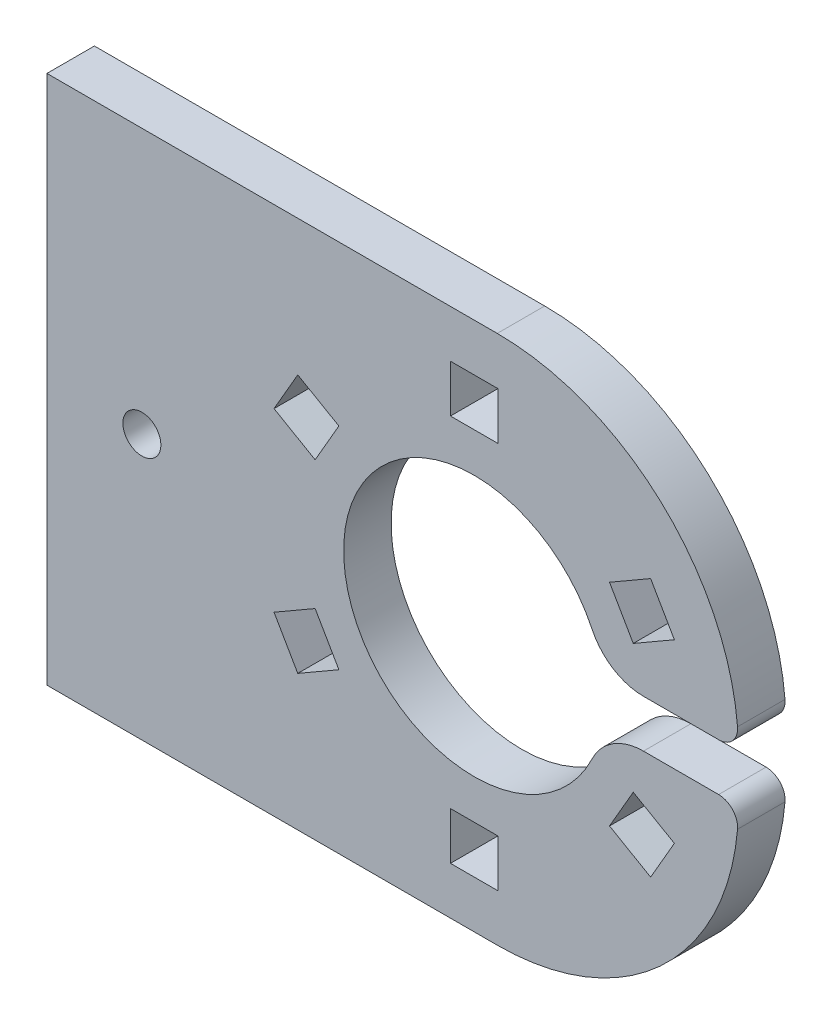
SolidWorks part; units mm, degrees
ref_plane "Plan de face" through (0, 0, 0) normal (0, 0, 1) x (1, 0, 0)
ref_plane "Plan de dessus" through (0, 0, 0) normal (0, 1, 0) x (1, 0, 0)
ref_plane "Plan de droite" through (0, 0, 0) normal (1, 0, 0) x (0, 0, -1)
sketch "Esquisse1" plane through (0, 0, 0) normal (0, 0, 1) x (1, 0, 0)
  line L0 (-62.8273, 27.9) -> (-62.8273, -27.9) construction
  line L1 (-72.8273, -27.9) -> (-72.8273, 27.9)
  line L2 (-52.8273, 27.9) -> (-52.8273, -27.9) construction
  line L4 (0, 2.5) -> (0, -2.5) construction
  line L5 (-72.8273, 27.9) -> (-25.4, 27.9)
  line L7 (-25.4, -27.9) -> (-72.8273, -27.9)
  line L17 (-60, 0) -> (0, 0) construction
  line L44 (-27.8273, 17.9) -> (-27.8273, 0) construction
  line L45 (-30.3273, 22.9) -> (-25.3273, 22.9)
  line L46 (-30.3273, 22.9) -> (-30.3273, 17.9)
  line L47 (-30.3273, 17.9) -> (-25.3273, 17.9)
  line L48 (-25.3273, 22.9) -> (-25.3273, 17.9)
  line L49 (-9.2453, 13.6151) -> (-6.7453, 9.2849)
  line L50 (-9.2453, 13.6151) -> (-13.5754, 11.1151)
  line L51 (-13.5754, 11.1151) -> (-11.0754, 6.7849)
  line L52 (-6.7453, 9.2849) -> (-11.0754, 6.7849)
  line L53 (-6.7453, -9.2849) -> (-9.2453, -13.6151)
  line L54 (-6.7453, -9.2849) -> (-11.0754, -6.7849)
  line L55 (-11.0754, -6.7849) -> (-13.5754, -11.1151)
  line L56 (-9.2453, -13.6151) -> (-13.5754, -11.1151)
  line L57 (-25.3273, -22.9) -> (-30.3273, -22.9)
  line L58 (-25.3273, -22.9) -> (-25.3273, -17.9)
  line L59 (-25.3273, -17.9) -> (-30.3273, -17.9)
  line L60 (-30.3273, -22.9) -> (-30.3273, -17.9)
  line L61 (-46.4093, -13.6151) -> (-48.9093, -9.2849)
  line L62 (-46.4093, -13.6151) -> (-42.0792, -11.1151)
  line L63 (-42.0792, -11.1151) -> (-44.5792, -6.7849)
  line L64 (-48.9093, -9.2849) -> (-44.5792, -6.7849)
  line L65 (-48.9093, 9.2849) -> (-46.4093, 13.6151)
  line L66 (-48.9093, 9.2849) -> (-44.5792, 6.7849)
  line L67 (-44.5792, 6.7849) -> (-42.0792, 11.1151)
  line L68 (-46.4093, 13.6151) -> (-42.0792, 11.1151)
  line L70 (0, 2.5) -> (-10, 2.5)
  line L71 (-10, -2.5) -> (0, -2.5)
  arc A0 (-25.4, 27.9) -> (0, 2.5) centre (-25.4, 2.5) cw
  arc A1 (-15.4159, 5.9177) -> (-15.4159, -5.9177) centre (-27.8273, 0) ccw
  arc A2 (-10, -2.5) -> (-15.4159, -5.9177) centre (-10, -8.5) ccw
  arc A3 (-10, 2.5) -> (-15.4159, 5.9177) centre (-10, 8.5) cw
  arc A4 (0, -2.5) -> (-25.4, -27.9) centre (-25.4, -2.5) cw
  circle A5 centre (-62.8273, 0) radius 2
  point P82 (-27.8273, 0)
  dimension "D10" = 27.5
  dimension "D17" = 6
  dimension "D5" = 45
  dimension "D2" = 10
  dimension "D7" = 4
  dimension "D3" = 5
  dimension "D4" = 10
  dimension "D6" = 10
  dimension "D11" = 17.9
  dimension "D12" = 5
  dimension "D13" = 6
  dimension "D15" = 5
extrude "Boss.-Extru.1" add sketch "Esquisse1" along normal blind 5
fillet "Congé1" radius 2 2 edges at (0, -2.5, 2.5) (0, 2.5, 2.5)
